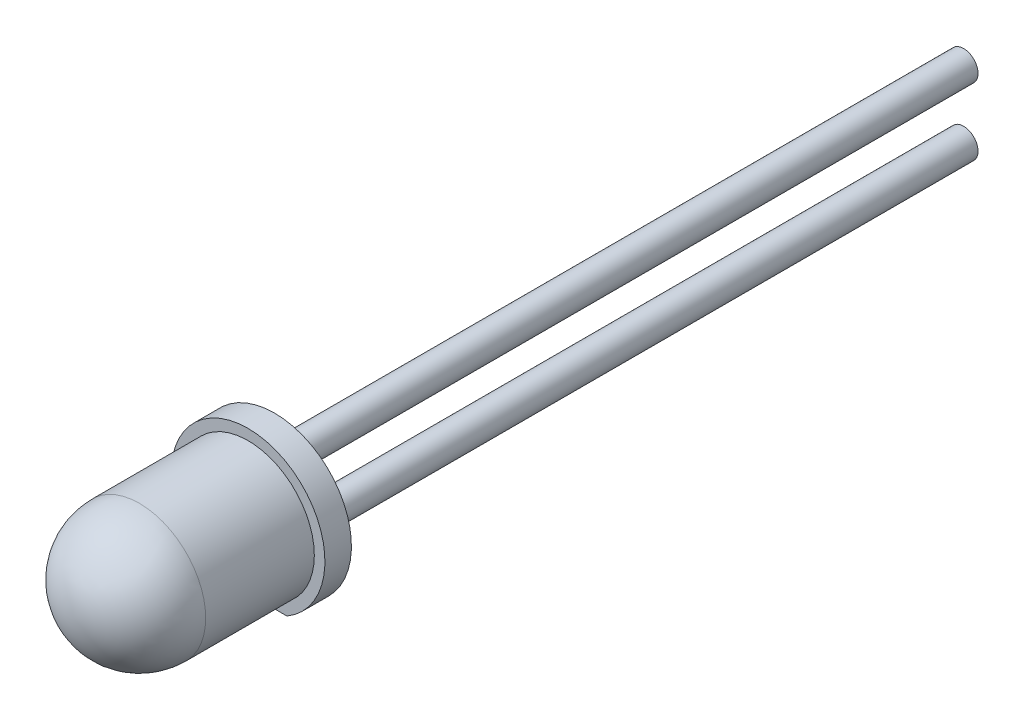
SolidWorks part; units mm, degrees
ref_plane "Front Plane" through (0, 0, 0) normal (0, 0, 1) x (1, 0, 0)
ref_plane "Top Plane" through (0, 0, 0) normal (0, 1, 0) x (1, 0, 0)
ref_plane "Right Plane" through (0, 0, 0) normal (1, 0, 0) x (0, 0, -1)
sketch "Sketch1" plane through (0, 0, 0) normal (1, 0, 0) x (0, 0, -1)
  line L0 (2.5, 2.5) -> (6.6, 2.5)
  line L1 (7.6, 2.7807) -> (7.6, 0)
  line L3 (6.6, 2.5) -> (6.6, 0)
  line L4 (6.6, 2.5) -> (6.6, 2.9)
  line L5 (6.6, 2.9) -> (7.6, 2.9)
  line L6 (7.6, 2.9) -> (7.6, 2.7807)
  line L7 (0, 0) -> (7.6, 0)
  arc A0 (0, 0) -> (2.5, 2.5) centre (2.5, 0) cw
  point P0 (0, 0)
  dimension "D1" = 7.6
  dimension "D2" = 2.5
  dimension "D3" = 1
  dimension "D4" = 2.9
revolve "Revolve1" add sketch "Sketch1" angle 360 about L7
sketch "Sketch2" plane through (0, 0, -7.6) normal (0, 0, -1) x (-1, 0, 0)
  line L0 (0, -1.27) -> (0, 1.27) construction
  circle A0 centre (0, 1.27) radius 0.545
  circle A1 centre (0, -1.27) radius 0.545
  point P0 (0, 0)
  point P4 (0, 0)
  point P8 (0, 0)
  point P10 (0, 0)
  point P11 (0, 0)
  point P12 (0, 0)
  dimension "D2" = 1.09
  dimension "D3" = 1.09
  dimension "D1" = 2.54
extrude "Boss-Extrude1" add sketch "Sketch2" along normal blind 26
ref_plane "Plane1" through (0, -2.5, 0) normal (0, -1, 0) x (-1, 0, 0)
sketch "Sketch3" plane through (0, -2.5, 0) normal (0, -1, 0) x (-1, 0, 0)
  line L1 (-15.6533, 19.1691) -> (6.0921, 19.1691)
  line L2 (-15.6533, 19.1691) -> (-15.6533, 3.0082)
  line L3 (-15.6533, 3.0082) -> (6.0921, 3.0082)
  line L4 (6.0921, 19.1691) -> (6.0921, 3.0082)
  line L5 (-15.6533, 19.1691) -> (6.0921, 3.0082) construction
  line L6 (-15.6533, 3.0082) -> (6.0921, 19.1691) construction
  point P0 (-4.7806, 11.0887)
extrude "Cut-Extrude1" cut sketch "Sketch3" along normal blind 660
fillet "Fillet1" radius 0.5 2 edges at (-0.545, 1.27, -7.6) (-0.545, -1.27, -7.6)
